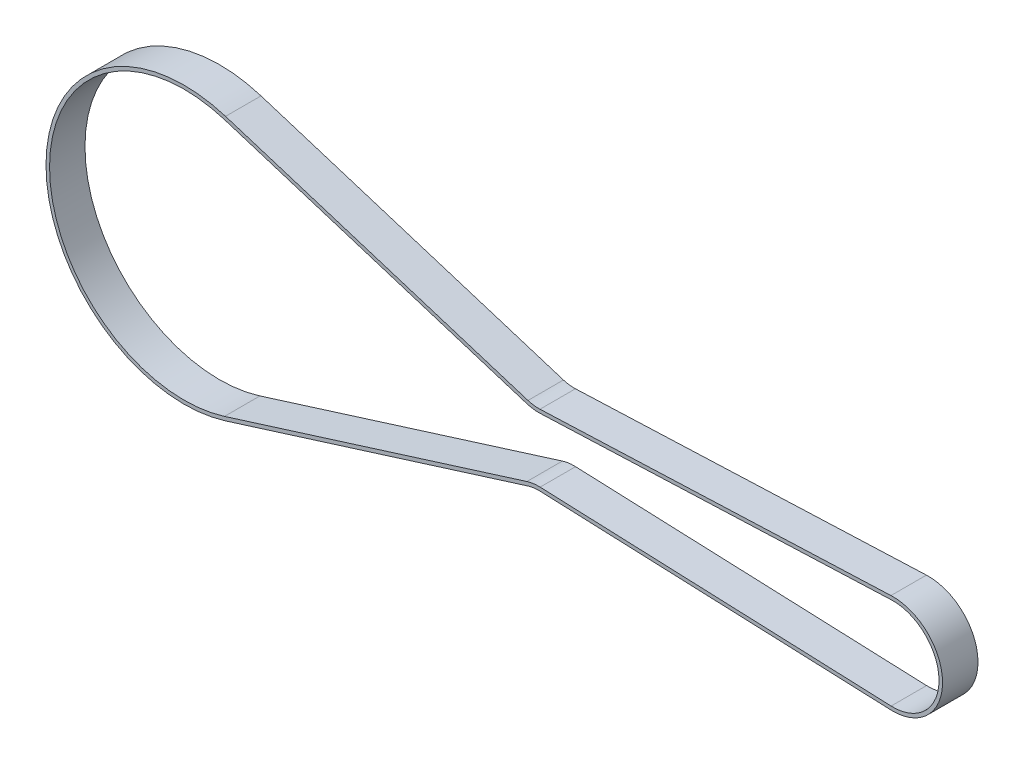
SolidWorks part; units mm, degrees
material "Caoutchouc"
ref_plane "Plan de face" through (0, 0, 0) normal (0, 0, 1) x (1, 0, 0)
ref_plane "Plan de dessus" through (0, 0, 0) normal (0, 1, 0) x (1, 0, 0)
ref_plane "Plan de droite" through (0, 0, 0) normal (1, 0, 0) x (0, 0, -1)
sketch "Esquisse1" plane through (0, 0, 0) normal (0, 0, 1) x (1, 0, 0)
  line L2 (-215.6391, -21.7184) -> (-15.6391, -21.7184) construction
  line L3 (-204.2711, 14.5413) -> (-118.9299, -12.2146)
  line L4 (-16.1612, -8.7289) -> (-115.1973, -12.7095)
  line L5 (-16.1612, -34.7079) -> (-115.1973, -30.7273)
  line L6 (-204.2711, -57.9781) -> (-118.9299, -31.2221)
  circle A0 centre (-215.6391, -21.7184) radius 38 construction
  circle A1 centre (-15.6391, -21.7184) radius 13 construction
  arc A2 (-204.2711, 14.5413) -> (-204.2711, -57.9781) centre (-215.6391, -21.7184) ccw
  arc A3 (-16.1612, -8.7289) -> (-16.1612, -34.7079) centre (-15.6391, -21.7184) cw
  arc A4 (-118.9299, -12.2146) -> (-115.1973, -12.7095) centre (-115.6391, -1.7184) ccw
  arc A5 (-118.9299, -31.2221) -> (-115.1973, -30.7273) centre (-115.6391, -41.7184) cw
  point P15 (0, 0)
  point P16 (0, 0)
  point P20 (-17.3461, -34.6603)
  dimension "D1" = 76
  dimension "D2" = 26
  dimension "D3" = 11
extrude "Extru.-Mince1" add sketch "Esquisse1" along normal blind 10 thin thin type one direction wall 1
